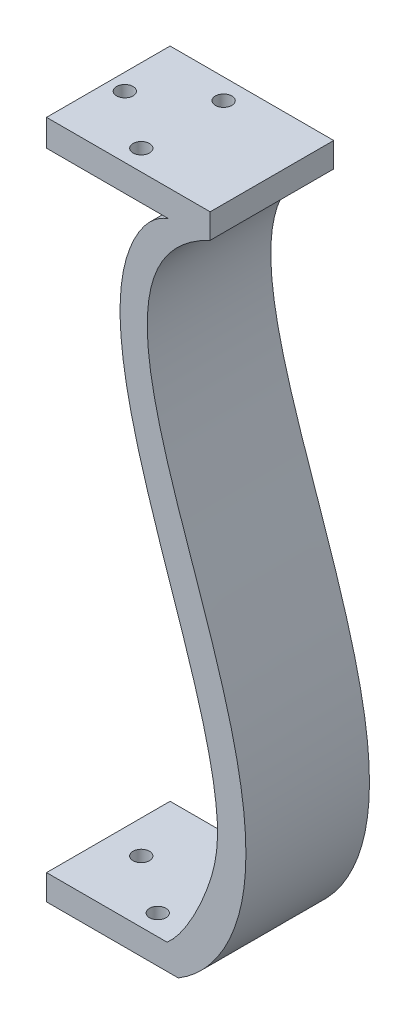
SolidWorks part; units mm, degrees
ref_plane "Front" through (0, 0, 0) normal (0, 0, 1) x (1, 0, 0)
ref_plane "Top" through (0, 0, 0) normal (0, 1, 0) x (1, 0, 0)
ref_plane "Right" through (0, 0, 0) normal (1, 0, 0) x (0, 0, -1)
sketch "Sketch1" plane through (0, 0, 0) normal (0, 1, 0) x (1, 0, 0)
  line L1 (0, 0) -> (-50, 0)
  line L2 (0, 0) -> (0, 30)
  line L3 (0, 30) -> (-50, 30)
  line L4 (-50, 0) -> (-50, 30)
  dimension "D1" = 50
  dimension "D2" = 30
extrude "block" add sketch "Sketch1" along normal blind 165
sketch "Sketch2" plane through (0, 0, 0) normal (0, 0, 1) x (1, 0, 0)
  line L1 (-50, 0) -> (0, 0) construction
  line L2 (-10.2669, 159) -> (-10.2669, 165)
  line L3 (-50, 165) -> (0, 165) construction
  line L4 (-18, 0) -> (0, 0)
  line L5 (0, 0) -> (0, 165)
  line L6 (0, 165) -> (-10.2669, 165)
  spline S0 degree 3 poles (-18, 0) (-10.6551, 4.4325) (21.0969, 53.2889) (-53.3339, 138.2792) (-10.2669, 159) knots 0 0 0 0 0.153176 1 1 1 1
  dimension "D1" = 6
  dimension "D2" = 18
extrude "Cut-Extrude1" cut sketch "Sketch2" against normal through all
sketch "Sketch3" plane through (0, 0, 0) normal (0, 0, 1) x (1, 0, 0)
  line L1 (-20.7199, 6.1656) -> (-50, 6.1656)
  line L2 (-50, 165) -> (-50, 0) construction
  line L3 (-20.3559, 158.5) -> (-50, 158.5)
  line L5 (-50, 165) -> (-10.2669, 165) construction
  spline S0 degree 3 poles (-20.7199, 6.1656) (-16.4171, 9.8799) (-8.5946, 25.2925) (-7.1245, 64.8232) (-46.2844, 128.9244) (-24.282, 157.1562) (-20.3559, 158.5) knots 0.052573 0.052573 0.052573 0.052573 0.159087 0.252212 0.902535 1 1 1 1
  dimension "D1" = 6.5
extrude "Cut-Extrude2" cut sketch "Sketch3" against normal through all and the other way through all
sketch "Sketch4" plane through (0, 0, 0) normal (0, -1, 0) x (1, 0, 0)
  line L0 (-50, -15) -> (-23.0693, -15) construction
  line L1 (-50, -30) -> (-50, 0) construction
  line L3 (-28, -3.0213) -> (-18, -3.0213) construction
  line L5 (-18, -30) -> (-18, 0) construction
  circle A0 centre (-42, -15) radius 2
  circle A1 centre (-28, -25) radius 2
  circle A2 centre (-28, -5) radius 2
  dimension "D1" = 4
  dimension "D3" = 10
  dimension "D2" = 10
  dimension "D4" = 14
extrude "Cut-Extrude3" cut sketch "Sketch4" against normal up to next
sketch "Sketch6" plane through (0, 165, 0) normal (0, 1, 0) x (1, 0, 0)
  line L0 (-50, 15) -> (-15.2551, 15) construction
  line L1 (-50, 30) -> (-50, 0) construction
  circle A0 centre (-46, 15) radius 2
  circle A1 centre (-32, 25) radius 2
  circle A2 centre (-32, 5) radius 2
  dimension "D1" = 4
  dimension "D2" = 4
  dimension "D3" = 4
  dimension "D5" = 20
  dimension "D4" = 14
  dimension "D6" = 4
extrude "Cut-Extrude10" cut sketch "Sketch6" against normal up to next
